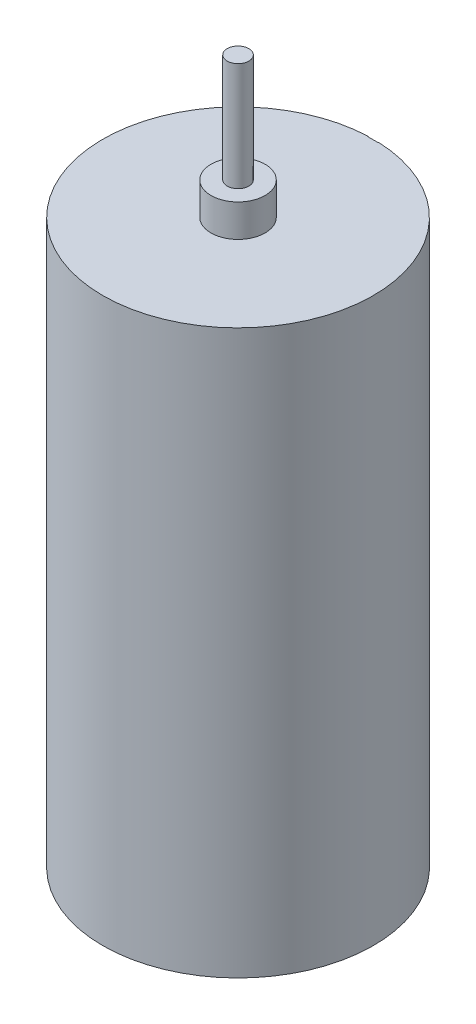
SolidWorks part; units mm, degrees
ref_plane "Alzado" through (0, 0, 0) normal (0, 0, 1) x (1, 0, 0)
ref_plane "Planta" through (0, 0, 0) normal (0, 1, 0) x (1, 0, 0)
ref_plane "Vista lateral" through (0, 0, 0) normal (1, 0, 0) x (0, 0, -1)
sketch "Croquis1" plane through (0, 0, 0) normal (0, 1, 0) x (1, 0, 0)
  circle A0 centre (0, 0) radius 12.5
  dimension "D1" = 25
extrude "Saliente-Extruir1" add sketch "Croquis1" along normal blind 52
sketch "Croquis2" plane through (0, 52, 0) normal (0, 1, 0) x (1, 0, 0)
  circle A0 centre (0, 0) radius 2.5
  dimension "D1" = 5
extrude "Saliente-Extruir2" add sketch "Croquis2" along normal blind 3
sketch "Croquis3" plane through (0, 55, 0) normal (0, 1, 0) x (1, 0, 0)
  circle A0 centre (0, 0) radius 1
  dimension "D1" = 2
extrude "Saliente-Extruir3" add sketch "Croquis3" along normal blind 10
sketch "Croquis4" plane through (0, 52, 0) normal (0, 1, 0) x (1, 0, 0)
  line L0 (0, -55) -> (0, 55) construction
  line L1 (-0.05, 12.55) -> (0.05, 12.55)
  line L2 (-0.05, 12.55) -> (-0.05, 12.45)
  line L3 (-0.05, 12.45) -> (0.05, 12.45)
  line L4 (0.05, 12.55) -> (0.05, 12.45)
  line L5 (-0.05, 12.55) -> (0.05, 12.45) construction
  line L6 (-0.05, 12.45) -> (0.05, 12.55) construction
  circle A0 centre (0, 0) radius 12.5 construction
  point P0 (0, 12.5)
  dimension "D1" = 0.1
  dimension "D2" = 0.1
extrude "Cortar-Extruir1" cut sketch "Croquis4" against normal blind 0.1
sketch "Croquis5" plane through (0, 52, 0) normal (0, 1, 0) x (1, 0, 0)
  line L1 (-0.5, 12.55) -> (0.5, 12.55)
  line L2 (-0.5, 12.55) -> (-0.5, 12.45)
  line L3 (-0.5, 12.45) -> (0.5, 12.45)
  line L4 (0.5, 12.55) -> (0.5, 12.45)
  line L5 (-0.5, 12.55) -> (0.5, 12.45) construction
  line L6 (-0.5, 12.45) -> (0.5, 12.55) construction
  arc A0 (0.05, 12.4999) -> (-0.05, 12.4999) centre (0, 0) ccw construction
  point P0 (0, 12.5)
  dimension "D1" = 1
  dimension "D2" = 0.1
extrude "Cortar-Extruir2" cut sketch "Croquis5" against normal blind 45
